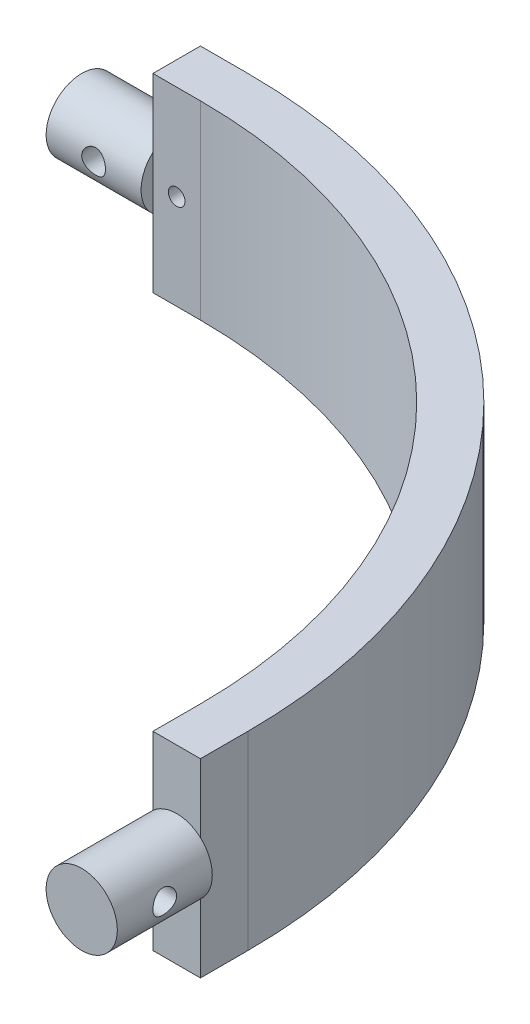
SolidWorks part; units mm, degrees
ref_plane "Front Plane" through (0, 0, 0) normal (0, 0, 1) x (1, 0, 0)
ref_plane "Top Plane" through (0, 0, 0) normal (0, 1, 0) x (1, 0, 0)
ref_plane "Right Plane" through (0, 0, 0) normal (1, 0, 0) x (0, 0, -1)
sketch "Sketch1" plane through (0, 0, 0) normal (0, 1, 0) x (1, 0, 0)
  line L0 (0, 152.4) -> (0, 139.7)
  line L1 (139.7, 0) -> (152.4, 0)
  arc A0 (139.7, 0) -> (0, 139.7) centre (0, 0) ccw
  arc A1 (152.4, 0) -> (0, 152.4) centre (0, 0) ccw
  dimension "D1" = 139.7
  dimension "D2" = 12.7
extrude "Boss-Extrude1" add sketch "Sketch1" along normal mid plane 50.8
sketch "Sketch2" plane through (0, 0, 0) normal (-1, 0, 0) x (0, 0, 1)
  line L1 (-152.4, 25.4) -> (-139.7, 25.4)
  line L2 (-152.4, 25.4) -> (-152.4, -25.4)
  line L3 (-152.4, -25.4) -> (-139.7, -25.4)
  line L4 (-139.7, 25.4) -> (-139.7, -25.4)
extrude "Boss-Extrude2" add sketch "Sketch2" along normal blind 12.7
sketch "Sketch3" plane through (0, 0, 0) normal (0, 0, 1) x (1, 0, 0)
  line L1 (139.7, 25.4) -> (152.4, 25.4)
  line L2 (139.7, 25.4) -> (139.7, -25.4)
  line L3 (139.7, -25.4) -> (152.4, -25.4)
  line L4 (152.4, 25.4) -> (152.4, -25.4)
extrude "Boss-Extrude3" add sketch "Sketch3" along normal blind 12.7
sketch "Sketch4" plane through (-12.7, 0, 0) normal (-1, 0, 0) x (0, 0, 1)
  line L1 (-139.7, 25.4) -> (-152.4, 25.4) construction
  line L2 (-139.7, 25.4) -> (-139.7, -25.4) construction
  circle A0 centre (-146.05, 0) radius 9.525
  point P6 (-169.1423, 30.0969)
  dimension "D3" = 19.05
  dimension "D1" = 25.4
  dimension "D2" = 6.35
extrude "Boss-Extrude4" add sketch "Sketch4" along normal blind 25.4
sketch "Sketch5" plane through (0, 0, -139.7) normal (0, 0, 1) x (1, 0, 0)
  line L0 (-38.1, 9.525) -> (-38.1, -9.525) construction
  line L1 (-12.7, 9.525) -> (-38.1, 9.525) construction
  circle A0 centre (-25.4, 0) radius 3.175
  dimension "D3" = 6.35
  dimension "D1" = 12.7
  dimension "D2" = 9.525
extrude "Cut-Extrude1" cut sketch "Sketch5" against normal mid plane 38.1
sketch "Sketch6" plane through (0, 0, 12.7) normal (0, 0, 1) x (1, 0, 0)
  line L0 (152.4, 25.4) -> (139.7, 25.4) construction
  line L1 (139.7, 25.4) -> (139.7, -25.4) construction
  circle A0 centre (146.05, 0) radius 9.525
  dimension "D3" = 19.05
  dimension "D1" = 25.4
  dimension "D2" = 6.35
extrude "Boss-Extrude5" add sketch "Sketch6" along normal blind 25.4
sketch "Sketch7" plane through (139.7, 0, 0) normal (-1, 0, 0) x (0, 0, 1)
  line L0 (38.1, 9.525) -> (12.7, 9.525) construction
  line L1 (38.1, -9.525) -> (38.1, 9.525) construction
  circle A0 centre (25.4, 0) radius 3.175
  dimension "D3" = 6.35
  dimension "D1" = 9.525
  dimension "D2" = 12.7
extrude "Cut-Extrude2" cut sketch "Sketch7" against normal mid plane 38.1
sketch "Sketch8" plane through (0, 0, -139.7) normal (0, 0, 1) x (1, 0, 0)
  line L0 (0, 25.4) -> (0, -25.4) construction
  line L1 (-12.7, 25.4) -> (0, 25.4) construction
  circle A0 centre (-6.35, 0) radius 2.2225
  dimension "D3" = 4.445
  dimension "D1" = 6.35
  dimension "D2" = 25.4
extrude "Cut-Extrude3" cut sketch "Sketch8" against normal blind 11.43
sketch "Sketch9" plane through (139.7, 0, 0) normal (-1, 0, 0) x (0, 0, 1)
  line L0 (12.7, 25.4) -> (12.7, 7.0995) construction
  line L1 (12.7, 25.4) -> (0, 25.4) construction
  circle A0 centre (6.35, 0) radius 2.2225
  dimension "D3" = 4.445
  dimension "D1" = 6.35
  dimension "D2" = 25.4
extrude "Cut-Extrude4" cut sketch "Sketch9" against normal blind 11.43
